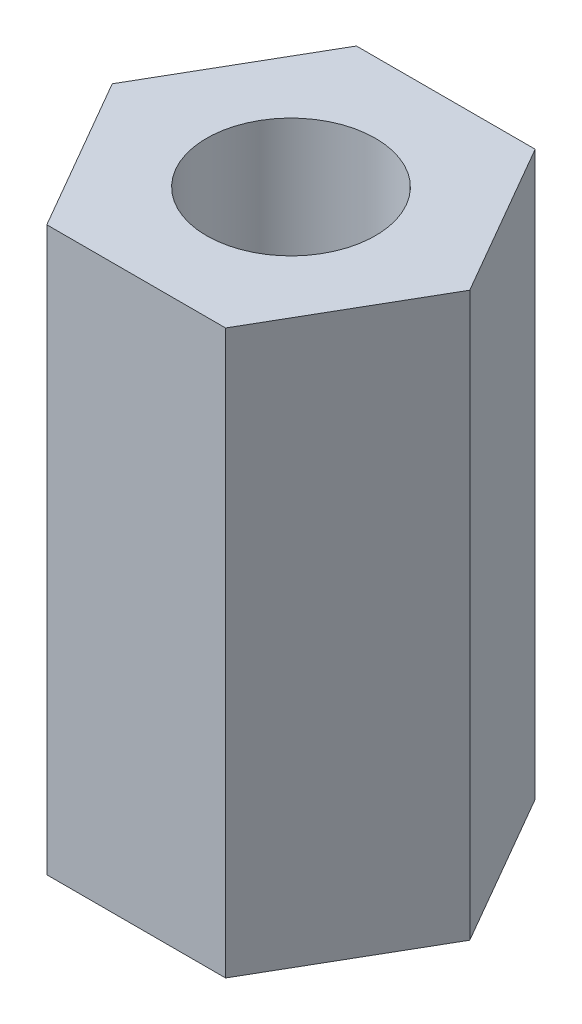
SolidWorks part; units mm, degrees
material "黄铜"
ref_plane "前视基准面" through (0, 0, 0) normal (0, 0, 1) x (1, 0, 0)
ref_plane "上视基准面" through (0, 0, 0) normal (0, 1, 0) x (1, 0, 0)
ref_plane "右视基准面" through (0, 0, 0) normal (1, 0, 0) x (0, 0, -1)
other "Configuration Table"
sketch "草图1" plane through (0, 0, 0) normal (0, 1, 0) x (1, 0, 0)
  line L1 (3.1754, 0) -> (1.5877, 2.75)
  line L2 (1.5877, 2.75) -> (-1.5877, 2.75)
  line L3 (-1.5877, 2.75) -> (-3.1754, 0)
  line L4 (-3.1754, 0) -> (-1.5877, -2.75)
  line L5 (-1.5877, -2.75) -> (1.5877, -2.75)
  line L6 (1.5877, -2.75) -> (3.1754, 0)
  circle A0 centre (0, 0) radius 2.75 construction
  circle A1 centre (0, 0) radius 1.5
  dimension "D1" = 5.5
  dimension "D2" = 3
extrude "凸台-拉伸1" add sketch "草图1" along normal blind 10
